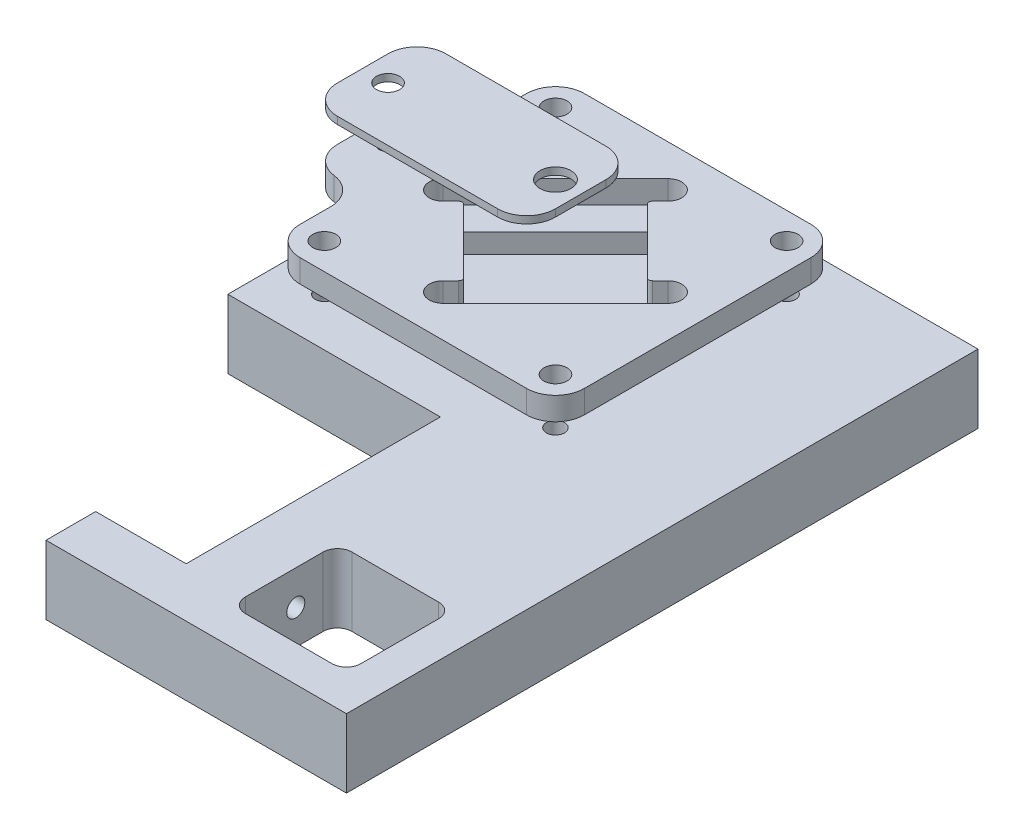
SolidWorks part; units mm, degrees
material "AISI 1045 Steel, cold drawn"
ref_plane "Front Plane" through (0, 0, 0) normal (0, 0, 1) x (1, 0, 0)
ref_plane "Top Plane" through (0, 0, 0) normal (0, 1, 0) x (1, 0, 0)
ref_plane "Right Plane" through (0, 0, 0) normal (1, 0, 0) x (0, 0, -1)
sketch "Sketch1" plane through (0, 0, 0) normal (0, 1, 0) x (1, 0, 0)
  line L0 (-211.9, -221.9) -> (-183.9, -221.9) construction
  line L1 (250, -250) -> (-250, -250)
  line L2 (250, -250) -> (250, 250)
  line L3 (250, 250) -> (-250, 250)
  line L4 (-250, -250) -> (-250, 250)
  line L5 (250, -250) -> (-250, 250) construction
  line L6 (250, 250) -> (-250, -250) construction
  line L7 (-250, -250) -> (-211.9, -250)
  line L8 (-250, -250) -> (-250, -211.9)
  line L9 (-250, -211.9) -> (-211.9, -211.9)
  line L10 (-211.9, -250) -> (-211.9, -211.9)
  line L11 (-211.9, -239) -> (-183.9, -239)
  line L12 (-211.9, -239) -> (-211.9, -204.8)
  line L13 (-211.9, -204.8) -> (-183.9, -204.8)
  line L14 (-183.9, -239) -> (-183.9, -204.8)
  line L16 (152.5, 152.5) -> (-152.5, 152.5)
  line L17 (152.5, 152.5) -> (152.5, -152.5)
  line L18 (152.5, -152.5) -> (-152.5, -152.5)
  line L19 (-152.5, 152.5) -> (-152.5, -152.5)
  line L20 (152.5, 152.5) -> (-152.5, -152.5) construction
  line L21 (152.5, -152.5) -> (-152.5, 152.5) construction
  point P0 (0, 0)
  point P15 (-158.3, -233)
  point P16 (-188.9, -188.9)
  point P17 (0, 0)
  point P22 (-181.1218, -181.1218)
  dimension "D1" = 500
  dimension "D2" = 38.1
  dimension "D3" = 28
  dimension "D4" = 34.2
  dimension "D5" = 20
  dimension "D6" = 91.7
  dimension "D7" = 17
  dimension "D8" = 305
  dimension "D9" = 5
  dimension "D10" = 11
ref_plane "Plane1" through (-188.9, 0, 188.9) normal (-0.7071, 0, 0.7071) x (0.7071, 0, 0.7071)
sketch "Sketch3" plane through (-188.9, 0, 188.9) normal (-0.7071, 0, 0.7071) x (0.7071, 0, 0.7071)
  line L0 (-8.6603, -5) -> (8.6603, -5) construction
  line L1 (0, 0) -> (0, -5) construction
  line L2 (-8.6603, -5) -> (0, 0) construction
  line L3 (-6.7451, -6.607) -> (-8.6603, -5) construction
  line L4 (-6.7451, -6.607) -> (6.7451, -6.607)
  line L5 (-6.7451, -6.607) -> (-6.7451, -16.132)
  line L6 (-6.7451, -16.132) -> (6.7451, -16.132)
  line L7 (6.7451, -6.607) -> (6.7451, -16.132)
  line L8 (10.5754, -16.132) -> (13.5754, -16.132)
  line L9 (-10.5754, -6.607) -> (-13.5754, -6.607)
  line L10 (-10.5754, -6.607) -> (-10.5754, -16.132)
  line L11 (-10.5754, -16.132) -> (-13.5754, -16.132)
  line L12 (-13.5754, -6.607) -> (-13.5754, -16.132)
  line L13 (13.5754, -6.607) -> (13.5754, -16.132)
  line L14 (10.5754, -6.607) -> (13.5754, -6.607)
  line L15 (10.5754, -6.607) -> (10.5754, -16.132)
  circle A0 centre (0, 0) radius 7.5
  circle A1 centre (-8.6603, -5) radius 2.5
  circle A2 centre (8.6603, -5) radius 2.5
  point P20 (-10.5754, -3.393)
  dimension "D1" = 15
  dimension "D2" = 5
  dimension "D3" = 30
  dimension "D4" = 9.525
  dimension "D5" = 40
  dimension "D6" = 3
extrude "Boss-Extrude1" add sketch "Sketch3" against normal blind 22 contours L9 L12 L11 L10 | L7 L4 L5 L6 | L14 L15 L8 L13 | L4 A0
sketch "Sketch4" plane through (-188.9, 0, 188.9) normal (-0.7071, 0, 0.7071) x (0.7071, 0, 0.7071)
  line L1 (-13.5754, -16.132) -> (13.5754, -16.132)
  line L2 (-13.5754, -16.132) -> (-13.5754, -6.607)
  line L3 (-13.5754, -6.607) -> (13.5754, -6.607)
  line L4 (13.5754, -16.132) -> (13.5754, -6.607)
extrude "Boss-Extrude2" add sketch "Sketch4" along normal blind 3
sketch "Sketch5" plane through (-173.3437, 0, 173.3437) normal (0.7071, 0, -0.7071) x (-0.7071, 0, -0.7071)
  line L1 (-13.5754, -16.132) -> (13.5754, -16.132)
  line L2 (-13.5754, -16.132) -> (-13.5754, -6.607)
  line L3 (-13.5754, -6.607) -> (13.5754, -6.607)
  line L4 (13.5754, -16.132) -> (13.5754, -6.607)
extrude "Boss-Extrude3" add sketch "Sketch5" along normal blind 3
sketch "Sketch7" plane through (0, -6.607, 0) normal (0, 1, 0) x (1, 0, 0)
  line L0 (-186.9, -239) -> (-183.9, -239)
  line L1 (-211.9, -239) -> (-183.9, -239) construction
  line L2 (-183.9, -239) -> (-183.9, -203.8)
  line L4 (-186.9, -239) -> (-186.9, -245.88)
  line L5 (-186.9, -245.88) -> (-145.3, -245.88)
  line L13 (-184.6015, -203.8) -> (-161.6231, -180.8216)
  line L15 (-183.9, -203.8) -> (-200.6206, -203.8)
  line L33 (-200.6206, -203.8) -> (-200.6206, -181.4221)
  line L34 (-200.6206, -181.4221) -> (-178.2426, -203.8)
  line L35 (-211.9, -204.8) -> (-183.9, -204.8) construction
  line L37 (-150.3, -239.88) -> (-166.3, -239.88) construction
  line L38 (-150.3, -239.88) -> (-150.3, -226.12)
  line L39 (-150.3, -226.12) -> (-166.3, -226.12)
  line L40 (-166.3, -239.88) -> (-166.3, -226.12)
  line L41 (-150.3, -239.88) -> (-166.3, -226.12) construction
  line L42 (-150.3, -226.12) -> (-166.3, -239.88) construction
  line L44 (-145.3, -161.6231) -> (-145.3, -245.88)
  line L45 (-166.3, -239.88) -> (-166.3, -240.88)
  line L46 (-166.3, -240.88) -> (-150.3, -240.88)
  line L47 (-150.3, -240.88) -> (-150.3, -239.88)
  line L48 (-181.4221, -200.6206) -> (-200.6206, -181.4221) construction
  line L49 (-181.4221, -200.6206) -> (-161.6231, -180.8216) construction
  line L50 (-161.6231, -180.8216) -> (-180.8216, -161.6231)
  line L51 (-180.8216, -161.6231) -> (-145.3, -161.6231)
  point P17 (-158.3, -233)
  dimension "D3" = 1
  dimension "D4" = 13.76
  dimension "D1" = 3
  dimension "D2" = 1
  dimension "D5" = 16
  dimension "D7" = 5
  dimension "D8" = 5
extrude "Boss-Extrude4" add sketch "Sketch7" against normal up to surface (9.525 mm away) up to face at (-181.1218, -16.132, 181.1218)
sketch "Sketch8" plane through (0, -6.607, 0) normal (0, 1, 0) x (1, 0, 0)
  line L1 (-183.9, -239) -> (-174.375, -239)
  line L2 (-183.9, -239) -> (-183.9, -203.8)
  line L3 (-183.9, -203.8) -> (-174.375, -203.8)
  line L4 (-174.375, -239) -> (-174.375, -203.8)
  dimension "D1" = 9.525
extrude "Cut-Extrude1" cut sketch "Sketch8" against normal up to surface (9.525 mm away) up to face at (-179.3625, -16.132, 209.1143)
hole_wizard "Tap Drill for M3x0.5 Tap1" positions "Sketch9" profile "Sketch11" hole size "M3x0.5" standard "ANSI Metric"
sketch "Sketch9" plane through (-174.375, 0, 0) normal (-1, 0, 0) x (0, 0, 1)
  line L0 (231.9, -11.3695) -> (211.9, -11.3695) construction
  line L6 (221.9, -6.607) -> (221.9, -16.132) construction
  line L7 (239, -6.607) -> (203.8, -6.607) construction
  line L8 (203.8, -16.132) -> (239, -16.132) construction
  point P2 (211.9, -11.3695)
  point P58 (231.9, -11.3695)
  point P59 (221.9, -11.3695)
  point P89 (221.9, -11.3695)
  dimension "D1" = 20
sketch "Sketch11" plane through (-174.375, -11.3695, 211.9) normal (0, 1, 0) x (0, 0, 1)
  line L0 (0, 0) -> (0, 10.7511)
  line L1 (0, 10.7511) -> (1.25, 10)
  line L2 (1.25, 10) -> (1.25, 0)
  line L5 (1.25, 0) -> (0, 0)
  line L10 (0, 10.7511) -> (-1.25, 10) construction
  line L11 (0, -6.35) -> (0, 107.95) construction
  dimension "Hole Dia." = 2.5
  dimension "Hole Depth" = 10
  dimension "Drill Angle" = 118
sketch "Sketch13" plane through (0, -6.607, 0) normal (0, 1, 0) x (1, 0, 0)
  line L2 (-181.4221, -196.3779) -> (-181.4221, -203.8) construction
  line L3 (-200.6206, -203.8) -> (-203.8, -203.8)
  line L4 (-200.6206, -203.8) -> (-200.6206, -181.4221)
  line L5 (-180.8216, -161.6231) -> (-200.6206, -181.4221)
  line L7 (-203.8, -203.8) -> (-203.8, -158.4437)
  line L8 (-174.375, -203.8) -> (-200.6206, -203.8) construction
  line L9 (-196.3779, -181.4221) -> (-203.8, -181.4221) construction
  line L10 (-180.8216, -165.8657) -> (-180.8216, -158.4437) construction
  line L11 (-180.8216, -161.6231) -> (-145.3, -161.6231)
  line L12 (-145.3, -161.6231) -> (-145.3, -158.4437)
  line L13 (-145.3, -158.4437) -> (-203.8, -158.4437)
extrude "Boss-Extrude5" add sketch "Sketch13" against normal up to surface (9.525 mm away) up to face at (-177.2459, -16.132, 209.1143)
sketch "Sketch15" plane through (0, -6.607, 0) normal (0, 1, 0) x (1, 0, 0)
  line L0 (-180.8216, -165.8657) -> (-178.1132, -168.5741) construction
  line L5 (-168.5741, -178.1132) -> (-165.8657, -180.8216) construction
  line L10 (-193.6695, -184.1305) -> (-196.3779, -181.4221) construction
  line L11 (-181.4221, -196.3779) -> (-184.1305, -193.6695) construction
  circle A8 centre (-179.4674, -167.2199) radius 1.9151
  circle A9 centre (-167.2199, -179.4674) radius 1.9151
  circle A10 centre (-195.0237, -182.7763) radius 1.9151
  circle A11 centre (-182.7763, -195.0237) radius 1.9151
extrude "Cut-Extrude4" cut sketch "Sketch15" against normal through all
fillet "Fillet4" radius 2 4 edges at (-150.3, -11.3695, 226.12) (-150.3, -11.3695, 240.88) (-166.3, -11.3695, 240.88) (-166.3, -11.3695, 226.12)
ref_plane "Plane2" through (0, -3.393, 0) normal (0, 1, 0) x (1, 0, 0)
sketch "Sketch22" plane through (0, -3.393, 0) normal (0, 1, 0) x (1, 0, 0)
  line L1 (-180.8216, -165.8657) -> (-196.3779, -181.4221) construction
  line L3 (-178.1132, -168.5741) -> (-193.6695, -184.1305) construction
  line L5 (-180.8216, -165.8657) -> (-196.3779, -181.4221)
  line L7 (-178.1132, -168.5741) -> (-179.5274, -169.9883)
  line L9 (-165.8657, -180.8216) -> (-181.4221, -196.3779) construction
  line L11 (-168.5741, -178.1132) -> (-184.1305, -193.6695) construction
  line L13 (-165.8657, -180.8216) -> (-181.4221, -196.3779)
  line L15 (-168.5741, -178.1132) -> (-169.9883, -179.5274)
  line L16 (-182.7163, -192.2553) -> (-192.2553, -182.7163)
  line L17 (-169.9883, -179.5274) -> (-179.5274, -169.9883)
  line L18 (-182.7163, -192.2553) -> (-184.1305, -193.6695)
  line L19 (-192.2553, -182.7163) -> (-193.6695, -184.1305)
  line L24 (-174.375, -203.8) -> (-203.8, -203.8) construction
  line L25 (-161.4437, -200.8) -> (-200.8, -200.8)
  line L26 (-187.4858, -187.4858) -> (-174.7579, -174.7579) construction
  line L28 (-161.4437, -200.8) -> (-161.4437, -161.4437)
  line L29 (-161.4437, -161.4437) -> (-200.8, -161.4437)
  line L30 (-200.8, -200.8) -> (-200.8, -161.4437)
  line L31 (-161.4437, -200.8) -> (-200.8, -161.4437) construction
  line L32 (-161.4437, -161.4437) -> (-200.8, -200.8) construction
  arc A16 (-184.1305, -193.6695) -> (-181.4221, -196.3779) centre (-182.7763, -195.0237) ccw construction
  arc A17 (-196.3779, -181.4221) -> (-193.6695, -184.1305) centre (-195.0237, -182.7763) ccw construction
  arc A18 (-165.8657, -180.8216) -> (-168.5741, -178.1132) centre (-167.2199, -179.4674) ccw construction
  arc A19 (-178.1132, -168.5741) -> (-180.8216, -165.8657) centre (-179.4674, -167.2199) ccw construction
  arc A20 (-184.1305, -193.6695) -> (-181.4221, -196.3779) centre (-182.7763, -195.0237) ccw
  arc A21 (-196.3779, -181.4221) -> (-193.6695, -184.1305) centre (-195.0237, -182.7763) ccw
  arc A22 (-165.8657, -180.8216) -> (-168.5741, -178.1132) centre (-167.2199, -179.4674) ccw
  arc A23 (-178.1132, -168.5741) -> (-180.8216, -165.8657) centre (-179.4674, -167.2199) ccw
  point P6 (-200.2396, -162.004)
  point P28 (-181.1218, -181.1218)
  point P32 (-181.1218, -181.1218)
  point P36 (-181.1218, -181.1218)
  dimension "D1" = 18
  dimension "D2" = 3
extrude "Boss-Extrude7" add sketch "Sketch22" along normal blind 3.175 separate body
fillet "Fillet9" radius 0.5 4 edges at (-192.2553, -1.8055, 182.7163) (-182.7163, -1.8055, 192.2553) (-169.9883, -1.8055, 179.5274) (-179.5274, -1.8055, 169.9883)
hole_wizard "M3 Clearance Hole1" positions "Sketch24" profile "Sketch25" hole size "M3" standard "ANSI Metric"
sketch "Sketch24" plane through (0, -0.218, 0) normal (0, 1, 0) x (1, 0, 0)
  line L0 (-187.4858, -187.4858) -> (-174.7579, -174.7579) construction
  line L1 (-191.9018, -183.0698) -> (-183.0698, -191.9018) construction
  line L2 (-170.3419, -179.1738) -> (-179.1738, -170.3419) construction
  line L5 (-165.1218, -197.1218) -> (-197.1218, -197.1218)
  line L6 (-165.1218, -197.1218) -> (-165.1218, -165.1218)
  line L7 (-165.1218, -165.1218) -> (-197.1218, -165.1218)
  line L8 (-197.1218, -197.1218) -> (-197.1218, -165.1218)
  line L9 (-165.1218, -197.1218) -> (-197.1218, -165.1218) construction
  line L10 (-165.1218, -165.1218) -> (-197.1218, -197.1218) construction
  point P10 (-181.1218, -181.1218)
  point P11 (-197.1218, -165.1218)
  point P100 (-165.1218, -197.1218)
  point P101 (-165.1218, -165.1218)
  point P102 (-197.1218, -197.1218)
  dimension "D1" = 32
sketch "Sketch25" plane through (-197.1218, -0.218, 197.1218) normal (1, 0, 0) x (0, 0, 1)
  line L0 (0, 0) -> (0, 4.9614)
  line L1 (0, 4.9614) -> (1.6, 4)
  line L2 (1.6, 4) -> (1.6, 0)
  line L5 (1.6, 0) -> (0, 0)
  line L10 (0, 4.9614) -> (-1.6, 4) construction
  line L11 (0, -6.35) -> (0, 107.95) construction
  dimension "Hole Dia." = 3.2
  dimension "Hole Depth" = 4
  dimension "Drill Angle" = 118
ref_plane "Plane3" through (0, 7.143, 0) normal (0, 1, 0) x (1, 0, 0)
hole_wizard "Tap Drill for M3x0.5 Tap2" positions "Sketch26" profile "Sketch27" hole size "M3x0.5" standard "ANSI Metric" end condition up to next
sketch "Sketch26" plane through (0, -6.607, 0) normal (0, 1, 0) x (1, 0, 0)
  point P3 (-165.1218, -165.1218)
  point P9 (-197.1218, -197.1218)
  point P15 (-197.1218, -165.1218)
  point P18 (-165.1218, -197.1218)
sketch "Sketch27" plane through (-165.1218, -6.607, 165.1218) normal (1, 0, 0) x (0, 0, 1)
  line L0 (0, 0) -> (0, 9.525)
  line L1 (0, 9.525) -> (1.25, 9.525)
  line L2 (1.25, 9.525) -> (1.25, 0)
  line L5 (1.25, 0) -> (0, 0)
  line L11 (0, -6.35) -> (0, 107.95) construction
  dimension "Thru Hole Dia." = 2.5
  dimension "Thru Hole Depth" = 9.525
sketch "Sketch28" plane through (0, -0.218, 0) normal (0, 1, 0) x (1, 0, 0)
  line L0 (-200.8, -161.4437) -> (-200.8, -200.8) construction
  line L1 (-207.8, -188.6218) -> (-200.8, -188.6218)
  line L2 (-207.8, -188.6218) -> (-207.8, -173.6218)
  line L3 (-207.8, -173.6218) -> (-200.8, -173.6218)
  line L4 (-200.8, -188.6218) -> (-200.8, -173.6218)
  line L5 (-207.8, -188.6218) -> (-200.8, -173.6218) construction
  line L6 (-207.8, -173.6218) -> (-200.8, -188.6218) construction
  line L7 (-187.4858, -187.4858) -> (-174.7579, -174.7579) construction
  line L8 (-191.9018, -183.0698) -> (-183.0698, -191.9018) construction
  line L9 (-170.3419, -179.1738) -> (-179.1738, -170.3419) construction
  point P0 (-204.3, -181.1218)
  point P13 (-181.1218, -181.1218)
  dimension "D1" = 15
  dimension "D2" = 7
extrude "Boss-Extrude10" add sketch "Sketch28" against normal up to surface (3.175 mm away) up to face at (-197.1218, -3.393, 166.7218)
hole_wizard "Tap Drill for M3x0.5 Tap5" positions "Sketch29" profile "Sketch30" hole size "M3x0.5" standard "ANSI Metric" end condition up to next
sketch "Sketch29" plane through (0, -0.218, 0) normal (0, 1, 0) x (1, 0, 0)
  line L0 (-204.3, -173.6218) -> (-204.3, -188.6218) construction
  line L1 (-200.8, -173.6218) -> (-207.8, -173.6218) construction
  line L2 (-207.8, -188.6218) -> (-200.8, -188.6218) construction
  point P9 (-204.3, -181.1218)
sketch "Sketch30" plane through (-204.3, -0.218, 181.1218) normal (1, 0, 0) x (0, 0, 1)
  line L0 (0, 0) -> (0, 3.176)
  line L1 (0, 3.176) -> (1.25, 3.176)
  line L2 (1.25, 3.176) -> (1.25, 0)
  line L5 (1.25, 0) -> (0, 0)
  line L11 (0, -6.35) -> (0, 107.95) construction
  dimension "Thru Hole Dia." = 2.5
  dimension "Thru Hole Depth" = 3.176
fillet "Fillet10" radius 4 6 edges at (-200.8, -1.8055, 161.4437) (-161.4437, -1.8055, 161.4437) (-161.4437, -1.8055, 200.8) (-200.8, -1.8055, 200.8) (-207.8, -1.8055, 188.6218) (-207.8, -1.8055, 173.6218)
fillet "Fillet11" radius 4 2 edges at (-200.8, -1.8055, 173.6218) (-200.8, -1.8055, 188.6218)
sketch "Sketch31" plane through (0, 7.143, 0) normal (0, 1, 0) x (1, 0, 0)
  line L0 (-187.4858, -187.4858) -> (-174.7579, -174.7579) construction
  line L3 (-191.9018, -183.0698) -> (-183.0698, -191.9018) construction
  line L6 (-170.3419, -179.1738) -> (-179.1738, -170.3419) construction
  line L7 (-204.3, -181.1218) -> (-181.1218, -181.1218) construction
  line L8 (-207.8, -177.6218) -> (-207.8, -184.6218) construction
  line L9 (-177.6218, -188.6218) -> (-207.8, -188.6218)
  line L10 (-177.6218, -188.6218) -> (-177.6218, -173.6218)
  line L11 (-177.6218, -173.6218) -> (-207.8, -173.6218)
  line L12 (-207.8, -188.6218) -> (-207.8, -173.6218)
  line L13 (-177.6218, -188.6218) -> (-207.8, -173.6218) construction
  line L14 (-177.6218, -173.6218) -> (-207.8, -188.6218) construction
  point P6 (-181.1218, -181.1218)
  point P10 (-192.7109, -181.1218)
  dimension "D1" = 15
extrude "Boss-Extrude11" add sketch "Sketch31" against normal blind 1 separate body
hole_wizard "M3 Clearance Hole3" positions "Sketch32" profile "Sketch33" hole size "M3" standard "ANSI Metric" end condition up to next
sketch "Sketch32" plane through (0, 7.143, 0) normal (0, 1, 0) x (1, 0, 0)
  point P0 (-204.3, -181.1218)
sketch "Sketch33" plane through (-204.3, 7.143, 181.1218) normal (1, 0, 0) x (0, 0, 1)
  line L0 (0, 0) -> (0, 1.001)
  line L1 (0, 1.001) -> (1.6, 1.001)
  line L2 (1.6, 1.001) -> (1.6, 0)
  line L5 (1.6, 0) -> (0, 0)
  line L11 (0, -6.35) -> (0, 107.95) construction
  dimension "Thru Hole Dia." = 3.2
  dimension "Thru Hole Depth" = 1.001
hole_wizard "M4 Clearance Hole1" positions "Sketch34" profile "Sketch35" hole size "M4" standard "ANSI Metric" end condition up to next
sketch "Sketch34" plane through (0, 7.143, 0) normal (0, 1, 0) x (1, 0, 0)
  point P0 (-181.1218, -181.1218)
sketch "Sketch35" plane through (-181.1218, 7.143, 181.1218) normal (1, 0, 0) x (0, 0, 1)
  line L0 (0, 0) -> (0, 23.275)
  line L1 (0, 23.275) -> (2.15, 23.275)
  line L2 (2.15, 23.275) -> (2.15, 0)
  line L5 (2.15, 0) -> (0, 0)
  line L11 (0, -6.35) -> (0, 107.95) construction
  dimension "Thru Hole Dia." = 4.3
  dimension "Thru Hole Depth" = 23.275
fillet "Fillet12" radius 4 4 edges at (-177.6218, 6.643, 188.6218) (-177.6218, 6.643, 173.6218) (-207.8, 6.643, 173.6218) (-207.8, 6.643, 188.6218)
